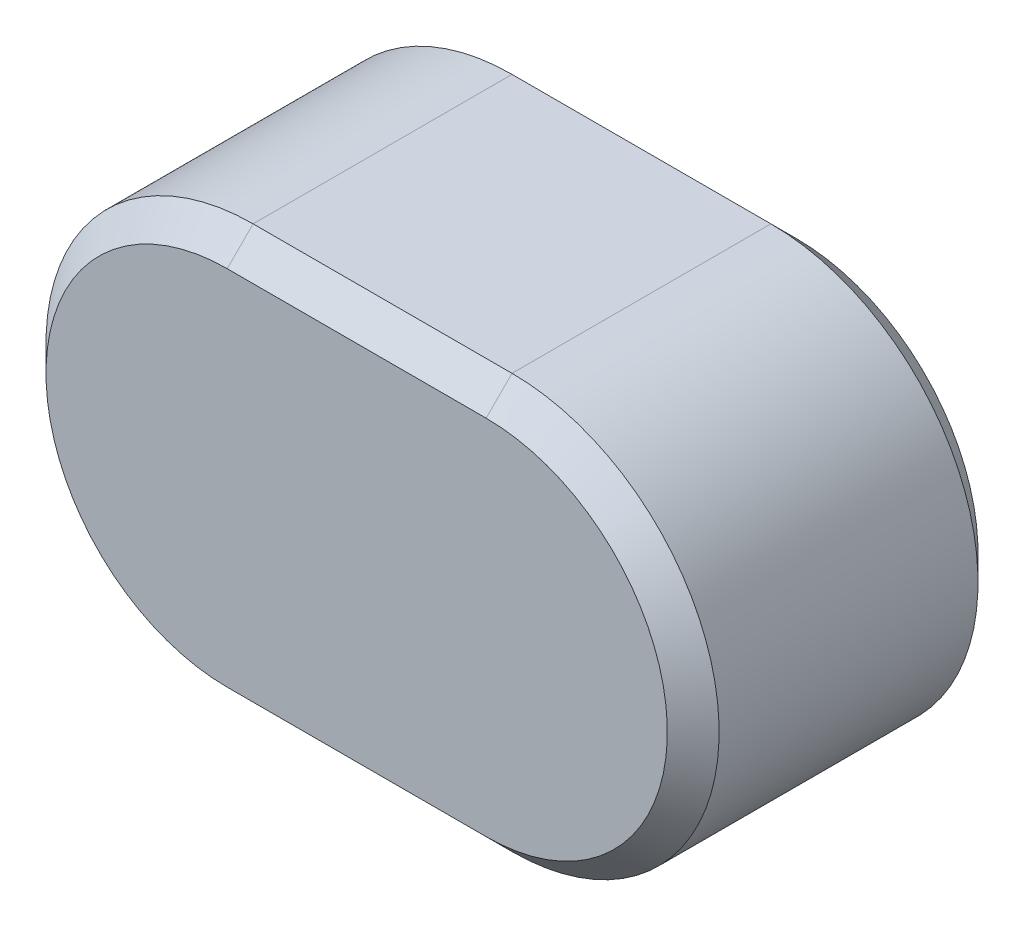
SolidWorks part; units mm, degrees
ref_plane "Piano frontale" through (0, 0, 0) normal (0, 0, 1) x (1, 0, 0)
ref_plane "Piano superiore" through (0, 0, 0) normal (0, 1, 0) x (1, 0, 0)
ref_plane "Piano destro" through (0, 0, 0) normal (1, 0, 0) x (0, 0, -1)
sketch "Schizzo1" plane through (0, 0, 0) normal (0, 0, 1) x (1, 0, 0)
  line L0 (-2.5, 0) -> (2.5, 0) construction
  line L1 (-2.5, 4) -> (2.5, 4)
  line L2 (-2.5, -4) -> (2.5, -4)
  arc A0 (-2.5, 4) -> (-2.5, -4) centre (-2.5, 0) ccw
  arc A1 (2.5, -4) -> (2.5, 4) centre (2.5, 0) ccw
  point P3 (0, 0)
  dimension "D1" = 5
  dimension "D2" = 8
extrude "Estrusione-Estrusione1" add sketch "Schizzo1" along normal blind 6
chamfer "Smusso1" distance 0.5 angle 45 8 edges at (0, -4, 0) (6.5, 0, 0) (-6.5, 0, 0) (0, 4, 0) (-6.5, 0, 6) (0, -4, 6) (0, 4, 6) (6.5, 0, 6)
